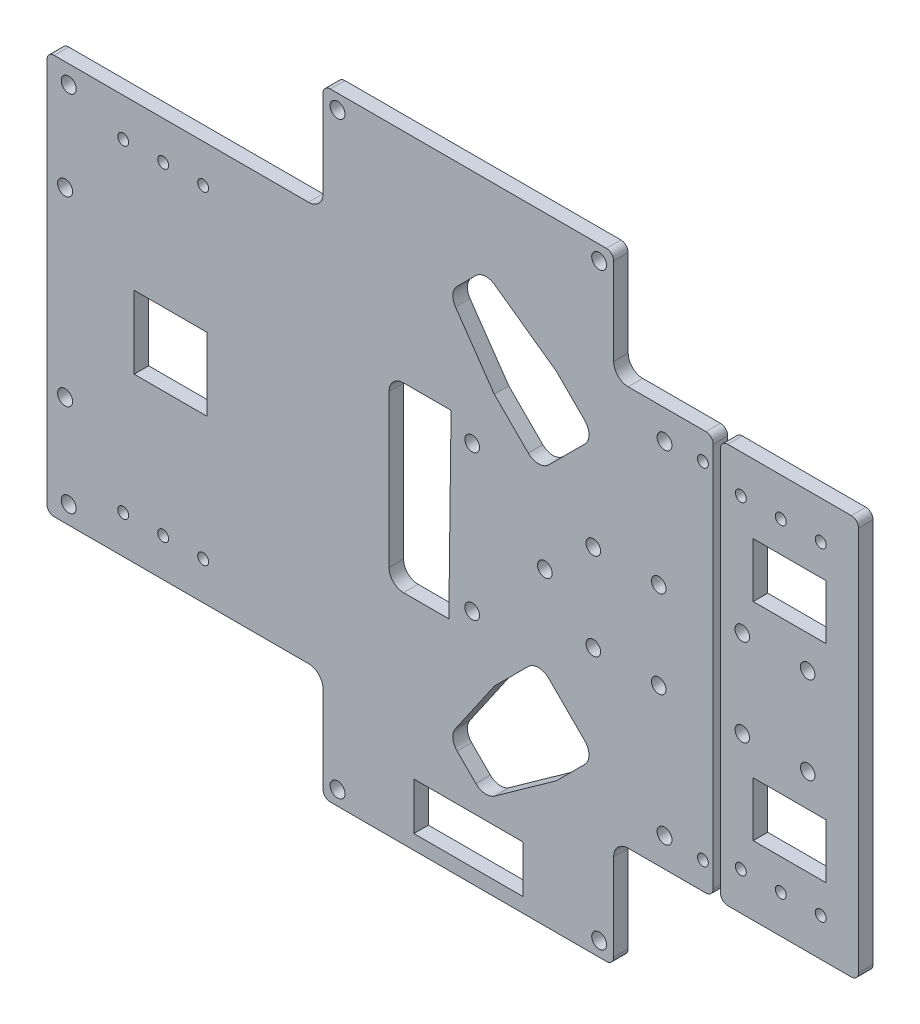
SolidWorks part; units mm, degrees
ref_plane "前视基准面" through (0, 0, 0) normal (0, 0, 1) x (1, 0, 0)
ref_plane "上视基准面" through (0, 0, 0) normal (0, 1, 0) x (1, 0, 0)
ref_plane "右视基准面" through (0, 0, 0) normal (1, 0, 0) x (0, 0, -1)
other "Configuration Table"
sketch "草图1" plane through (0, 0, 0) normal (0, 0, 1) x (1, 0, 0)
  line L12 (-3.0113, -94.6386) -> (-13.7106, -110.1444)
  line L13 (6.3168, -85.3106) -> (-3.0113, -94.6386)
  line L14 (21.8731, -95.21) -> (11.9736, -85.3106)
  line L15 (14.0949, -108.6451) -> (21.8731, -100.8669)
  line L16 (-2.9467, -120.8177) -> (14.0949, -108.6451)
  line L17 (-13.2467, -115.2445) -> (-8.1001, -120.3912)
  line L24 (-8.1001, 0.6818) -> (-13.2467, -4.4649)
  line L25 (14.0949, -11.0643) -> (-2.9467, 1.1083)
  line L26 (21.8731, -18.8425) -> (14.0949, -11.0643)
  line L27 (11.9736, -34.3989) -> (21.8731, -24.4994)
  line L28 (-3.0113, -25.0708) -> (6.3168, -34.3989)
  line L29 (-13.7106, -9.565) -> (-3.0113, -25.0708)
  line L34 (-14.948, -34.8547) -> (-27.9838, -34.8547)
  line L35 (3.0162, -67.8547) -> (3.0162, -51.8547)
  line L36 (-1.2427, -71.8547) -> (-0.9838, -71.8547)
  line L37 (-27.9838, -84.8547) -> (-15.207, -84.8547)
  line L38 (-31.9838, -38.8547) -> (-31.9838, -80.8547)
  line L42 (-82.1538, -49.8547) -> (-102.1538, -49.8547)
  line L43 (-82.1538, -69.8547) -> (-82.1538, -49.8547)
  line L44 (-102.1538, -69.8547) -> (-82.1538, -69.8547)
  line L45 (-102.1538, -49.8547) -> (-102.1538, -69.8547)
  line L50 (4.8462, -140.8547) -> (4.8462, -127.8547)
  line L51 (-25.1538, -140.8547) -> (4.8462, -140.8547)
  line L52 (-25.1538, -127.8547) -> (-25.1538, -140.8547)
  line L53 (4.8462, -127.8547) -> (-25.1538, -127.8547)
  line L70 (88.2462, -80.8547) -> (68.2462, -80.8547)
  line L71 (88.2462, -95.8547) -> (88.2462, -80.8547)
  line L72 (68.2462, -95.8547) -> (88.2462, -95.8547)
  line L73 (68.2462, -80.8547) -> (68.2462, -95.8547)
  line L74 (27.8462, 25.1453) -> (-48.1538, 25.1453)
  line L75 (-50.1538, 23.1453) -> (-50.1538, -0.8547)
  line L76 (-54.1538, -4.8547) -> (-124.1538, -4.8547)
  line L77 (-126.1538, -6.8547) -> (-126.1538, -112.8547)
  line L78 (-124.1538, -114.8547) -> (-54.1538, -114.8547)
  line L79 (-50.1538, -118.8547) -> (-50.1538, -142.8547)
  line L80 (-48.1538, -144.8547) -> (27.8462, -144.8547)
  line L81 (29.8462, -142.8547) -> (29.8462, -118.8547)
  line L82 (33.8462, -114.8547) -> (55.2462, -114.8547)
  line L83 (57.2462, -112.8547) -> (57.2462, -6.8547)
  line L84 (55.2462, -4.8547) -> (33.8462, -4.8547)
  line L85 (29.8462, -0.8547) -> (29.8462, 23.1453)
  line L90 (88.2462, -38.8547) -> (88.2462, -23.8547)
  line L91 (68.2462, -38.8547) -> (88.2462, -38.8547)
  line L92 (68.2462, -23.8547) -> (68.2462, -38.8547)
  line L93 (88.2462, -23.8547) -> (68.2462, -23.8547)
  line L98 (95.2462, -4.8547) -> (61.2462, -4.8547)
  line L99 (59.2462, -6.8547) -> (59.2462, -112.8547)
  line L100 (61.2462, -114.8547) -> (95.2462, -114.8547)
  line L101 (97.2462, -112.8547) -> (97.2462, -6.8547)
  arc A4 (-94.1538, -102.8547) -> (-94.1538, -105.8547) centre (-94.1538, -104.3547) ccw
  arc A5 (-94.1538, -105.8547) -> (-94.1538, -102.8547) centre (-94.1538, -104.3547) ccw
  arc A8 (-46.1538, 23.1953) -> (-46.1538, 19.0953) centre (-46.1538, 21.1453) ccw
  arc A9 (-46.1538, 19.0953) -> (-46.1538, 23.1953) centre (-46.1538, 21.1453) ccw
  arc A12 (25.8462, 23.1953) -> (25.8462, 19.0953) centre (25.8462, 21.1453) ccw
  arc A13 (25.8462, 19.0953) -> (25.8462, 23.1953) centre (25.8462, 21.1453) ccw
  arc A16 (43.8462, -10.8047) -> (43.8462, -14.9047) centre (43.8462, -12.8547) ccw
  arc A17 (43.8462, -14.9047) -> (43.8462, -10.8047) centre (43.8462, -12.8547) ccw
  arc A20 (-15.6538, -89.8047) -> (-15.6538, -93.9047) centre (-15.6538, -91.8547) ccw
  arc A21 (-15.6538, -93.9047) -> (-15.6538, -89.8047) centre (-15.6538, -91.8547) ccw
  arc A24 (43.8462, -104.8047) -> (43.8462, -108.9047) centre (43.8462, -106.8547) ccw
  arc A25 (43.8462, -108.9047) -> (43.8462, -104.8047) centre (43.8462, -106.8547) ccw
  arc A28 (25.8462, -138.8047) -> (25.8462, -142.9047) centre (25.8462, -140.8547) ccw
  arc A29 (25.8462, -142.9047) -> (25.8462, -138.8047) centre (25.8462, -140.8547) ccw
  arc A32 (-46.1538, -138.8047) -> (-46.1538, -142.9047) centre (-46.1538, -140.8547) ccw
  arc A33 (-46.1538, -142.9047) -> (-46.1538, -138.8047) centre (-46.1538, -140.8547) ccw
  arc A42 (9.1452, -84.139) -> (6.3168, -85.3106) centre (9.1452, -88.139) ccw
  arc A43 (11.9736, -85.3106) -> (9.1452, -84.139) centre (9.1452, -88.139) ccw
  arc A44 (21.8731, -100.8669) -> (21.8731, -95.21) centre (19.0447, -98.0385) ccw
  arc A45 (-8.1001, -120.3912) -> (-2.9467, -120.8177) centre (-5.2717, -117.5627) ccw
  arc A46 (-13.7106, -110.1444) -> (-13.2467, -115.2445) centre (-10.4183, -112.4161) ccw
  arc A51 (54.4053, -13.8547) -> (54.4053, -10.8547) centre (54.4053, -12.3547) ccw
  arc A52 (-5.2717, 1.8533) -> (-8.1001, 0.6818) centre (-5.2717, -2.1467) ccw
  arc A53 (-2.9467, 1.1083) -> (-5.2717, 1.8533) centre (-5.2717, -2.1467) ccw
  arc A54 (21.8731, -24.4994) -> (21.8731, -18.8425) centre (19.0447, -21.6709) ccw
  arc A55 (6.3168, -34.3989) -> (11.9736, -34.3989) centre (9.1452, -31.5704) ccw
  arc A56 (-13.2467, -4.4649) -> (-13.7106, -9.565) centre (-10.4183, -7.2933) ccw
  arc A57 (54.4053, -10.8547) -> (54.4053, -13.8547) centre (54.4053, -12.3547) ccw
  arc A60 (54.4053, -108.8547) -> (54.4053, -105.8547) centre (54.4053, -107.3547) ccw
  arc A61 (54.4053, -105.8547) -> (54.4053, -108.8547) centre (54.4053, -107.3547) ccw
  arc A64 (24.2462, -73.8547) -> (24.2462, -69.8547) centre (24.2462, -71.8547) ccw
  arc A65 (24.2462, -69.8547) -> (24.2462, -73.8547) centre (24.2462, -71.8547) ccw
  arc A68 (42.2462, -49.8547) -> (42.2462, -45.8547) centre (42.2462, -47.8547) ccw
  arc A69 (42.2462, -45.8547) -> (42.2462, -49.8547) centre (42.2462, -47.8547) ccw
  arc A80 (-105.1538, -13.8547) -> (-105.1538, -16.8547) centre (-105.1538, -15.3547) ccw
  arc A81 (-105.1538, -16.8547) -> (-105.1538, -13.8547) centre (-105.1538, -15.3547) ccw
  arc A84 (-4.9736, -44.1404) -> (-14.948, -34.8547) centre (-14.948, -44.8547) ccw
  arc A85 (-4.9736, -44.1404) -> (-0.9838, -47.8547) centre (-0.9838, -43.8547) ccw
  arc A86 (3.0162, -51.8547) -> (-0.9838, -47.8547) centre (-0.9838, -51.8547) ccw
  arc A87 (-0.9838, -71.8547) -> (3.0162, -67.8547) centre (-0.9838, -67.8547) ccw
  arc A88 (-1.2427, -71.8547) -> (-5.2325, -75.569) centre (-1.2427, -75.8547) ccw
  arc A89 (-15.207, -84.8547) -> (-5.2325, -75.569) centre (-15.207, -74.8547) ccw
  arc A90 (-31.9838, -80.8547) -> (-27.9838, -84.8547) centre (-27.9838, -80.8547) ccw
  arc A91 (-27.9838, -34.8547) -> (-31.9838, -38.8547) centre (-27.9838, -38.8547) ccw
  arc A92 (-94.1538, -13.8547) -> (-94.1538, -16.8547) centre (-94.1538, -15.3547) ccw
  arc A93 (-94.1538, -16.8547) -> (-94.1538, -13.8547) centre (-94.1538, -15.3547) ccw
  arc A96 (-83.1538, -13.8547) -> (-83.1538, -16.8547) centre (-83.1538, -15.3547) ccw
  arc A97 (-83.1538, -16.8547) -> (-83.1538, -13.8547) centre (-83.1538, -15.3547) ccw
  arc A100 (-83.1538, -102.8547) -> (-83.1538, -105.8547) centre (-83.1538, -104.3547) ccw
  arc A101 (-83.1538, -105.8547) -> (-83.1538, -102.8547) centre (-83.1538, -104.3547) ccw
  arc A104 (-15.6538, -25.8047) -> (-15.6538, -29.9047) centre (-15.6538, -27.8547) ccw
  arc A105 (-15.6538, -29.9047) -> (-15.6538, -25.8047) centre (-15.6538, -27.8547) ccw
  arc A108 (42.2462, -69.8547) -> (42.2462, -73.8547) centre (42.2462, -71.8547) ccw
  arc A109 (42.2462, -73.8547) -> (42.2462, -69.8547) centre (42.2462, -71.8547) ccw
  arc A112 (-120.1538, -107.7947) -> (-120.1538, -111.9147) centre (-120.1538, -109.8547) ccw
  arc A113 (-120.1538, -111.9147) -> (-120.1538, -107.7947) centre (-120.1538, -109.8547) ccw
  arc A116 (-121.1538, -82.7947) -> (-121.1538, -86.9147) centre (-121.1538, -84.8547) ccw
  arc A117 (-121.1538, -86.9147) -> (-121.1538, -82.7947) centre (-121.1538, -84.8547) ccw
  arc A120 (-45.6538, -57.8047) -> (-45.6538, -61.9047) centre (-45.6538, -59.8547) ccw
  arc A121 (-45.6538, -61.9047) -> (-45.6538, -57.8047) centre (-45.6538, -59.8547) ccw
  arc A124 (24.2462, -45.8547) -> (24.2462, -49.8547) centre (24.2462, -47.8547) ccw
  arc A125 (24.2462, -49.8547) -> (24.2462, -45.8547) centre (24.2462, -47.8547) ccw
  arc A128 (-121.1538, -32.7947) -> (-121.1538, -36.9147) centre (-121.1538, -34.8547) ccw
  arc A129 (-121.1538, -36.9147) -> (-121.1538, -32.7947) centre (-121.1538, -34.8547) ccw
  arc A132 (-120.1538, -7.7947) -> (-120.1538, -11.9147) centre (-120.1538, -9.8547) ccw
  arc A133 (-120.1538, -11.9147) -> (-120.1538, -7.7947) centre (-120.1538, -9.8547) ccw
  arc A136 (-105.1538, -102.8547) -> (-105.1538, -105.8547) centre (-105.1538, -104.3547) ccw
  arc A137 (-105.1538, -105.8547) -> (-105.1538, -102.8547) centre (-105.1538, -104.3547) ccw
  arc A152 (86.8462, -13.8547) -> (86.8462, -16.8547) centre (86.8462, -15.3547) ccw
  arc A153 (86.8462, -16.8547) -> (86.8462, -13.8547) centre (86.8462, -15.3547) ccw
  arc A156 (65.2462, -45.8547) -> (65.2462, -49.8547) centre (65.2462, -47.8547) ccw
  arc A157 (65.2462, -49.8547) -> (65.2462, -45.8547) centre (65.2462, -47.8547) ccw
  arc A160 (-48.1538, 25.1453) -> (-50.1538, 23.1453) centre (-48.1538, 23.1453) ccw
  arc A161 (-54.1538, -4.8547) -> (-50.1538, -0.8547) centre (-54.1538, -0.8547) ccw
  arc A162 (-124.1538, -4.8547) -> (-126.1538, -6.8547) centre (-124.1538, -6.8547) ccw
  arc A163 (-126.1538, -112.8547) -> (-124.1538, -114.8547) centre (-124.1538, -112.8547) ccw
  arc A164 (-50.1538, -118.8547) -> (-54.1538, -114.8547) centre (-54.1538, -118.8547) ccw
  arc A165 (-50.1538, -142.8547) -> (-48.1538, -144.8547) centre (-48.1538, -142.8547) ccw
  arc A166 (27.8462, -144.8547) -> (29.8462, -142.8547) centre (27.8462, -142.8547) ccw
  arc A167 (33.8462, -114.8547) -> (29.8462, -118.8547) centre (33.8462, -118.8547) ccw
  arc A168 (55.2462, -114.8547) -> (57.2462, -112.8547) centre (55.2462, -112.8547) ccw
  arc A169 (57.2462, -6.8547) -> (55.2462, -4.8547) centre (55.2462, -6.8547) ccw
  arc A170 (29.8462, -0.8547) -> (33.8462, -4.8547) centre (33.8462, -0.8547) ccw
  arc A171 (29.8462, 23.1453) -> (27.8462, 25.1453) centre (27.8462, 23.1453) ccw
  arc A172 (64.8462, -13.8547) -> (64.8462, -16.8547) centre (64.8462, -15.3547) ccw
  arc A173 (64.8462, -16.8547) -> (64.8462, -13.8547) centre (64.8462, -15.3547) ccw
  arc A176 (75.8462, -13.8547) -> (75.8462, -16.8547) centre (75.8462, -15.3547) ccw
  arc A177 (75.8462, -16.8547) -> (75.8462, -13.8547) centre (75.8462, -15.3547) ccw
  arc A180 (86.8462, -102.8547) -> (86.8462, -105.8547) centre (86.8462, -104.3547) ccw
  arc A181 (86.8462, -105.8547) -> (86.8462, -102.8547) centre (86.8462, -104.3547) ccw
  arc A184 (75.8462, -102.8547) -> (75.8462, -105.8547) centre (75.8462, -104.3547) ccw
  arc A185 (75.8462, -105.8547) -> (75.8462, -102.8547) centre (75.8462, -104.3547) ccw
  arc A188 (64.8462, -102.8547) -> (64.8462, -105.8547) centre (64.8462, -104.3547) ccw
  arc A189 (64.8462, -105.8547) -> (64.8462, -102.8547) centre (64.8462, -104.3547) ccw
  arc A192 (83.2462, -49.8547) -> (83.2462, -45.8547) centre (83.2462, -47.8547) ccw
  arc A193 (83.2462, -45.8547) -> (83.2462, -49.8547) centre (83.2462, -47.8547) ccw
  arc A196 (65.2462, -73.8547) -> (65.2462, -69.8547) centre (65.2462, -71.8547) ccw
  arc A197 (65.2462, -69.8547) -> (65.2462, -73.8547) centre (65.2462, -71.8547) ccw
  arc A200 (83.2462, -69.8547) -> (83.2462, -73.8547) centre (83.2462, -71.8547) ccw
  arc A201 (83.2462, -73.8547) -> (83.2462, -69.8547) centre (83.2462, -71.8547) ccw
  arc A208 (61.2462, -4.8547) -> (59.2462, -6.8547) centre (61.2462, -6.8547) ccw
  arc A209 (59.2462, -112.8547) -> (61.2462, -114.8547) centre (61.2462, -112.8547) ccw
  arc A210 (95.2462, -114.8547) -> (97.2462, -112.8547) centre (95.2462, -112.8547) ccw
  arc A211 (97.2462, -6.8547) -> (95.2462, -4.8547) centre (95.2462, -6.8547) ccw
extrude "凸台-拉伸1" add sketch "草图1" against normal up to surface (4 mm away)
sketch "草图2" plane through (0, 0, 0) normal (0, 0, 1) x (1, 0, 0)
  line L0 (-14.8976, -33.4742) -> (-15.5492, -86.1914)
  line L1 (-15.5492, -86.1914) -> (5.1661, -81.3269)
  line L2 (5.1661, -81.3269) -> (9.3865, -59.8547)
  line L3 (9.3865, -59.8547) -> (9.3865, -46.9567)
  line L4 (9.3865, -46.9567) -> (-9.5834, -32.4006)
  line L5 (-9.5834, -32.4006) -> (-14.8976, -33.4742)
  point P5 (-14.8976, -33.4742)
  point P7 (0, 0)
  point P8 (-15.5492, -86.1914)
extrude "凸台-拉伸3" add sketch "草图2" against normal up to surface (4 mm away)
sketch "草图3" plane through (0, 0, 0) normal (0, 0, 1) x (1, 0, 0)
  circle A3 centre (-9.0975, -39.8309) radius 2.025
  circle A4 centre (-9.0975, -79.8309) radius 2.025
  circle A5 centre (10.9025, -59.8309) radius 2.025
extrude "切除-拉伸1" cut sketch "草图3" against normal up to next (4 mm away)
sketch "草图4" plane through (0, 0, 0) normal (0, 0, 1) x (1, 0, 0)
  circle A0 centre (-15.6538, -27.8547) radius 4.5344
  circle A1 centre (-45.6538, -59.8547) radius 5.1811
  circle A2 centre (-15.6538, -91.8547) radius 2.8754
extrude "凸台-拉伸4" add sketch "草图4" against normal up to surface (4 mm away) up to face at (-11.1225, -39.8309, -4)
